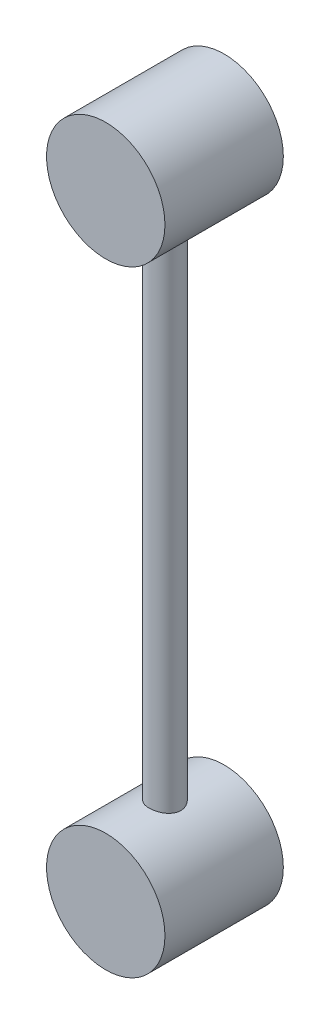
SolidWorks part; units mm, degrees
ref_plane "Front Plane" through (0, 0, 0) normal (0, 0, 1) x (1, 0, 0)
ref_plane "Top Plane" through (0, 0, 0) normal (0, 1, 0) x (1, 0, 0)
ref_plane "Right Plane" through (0, 0, 0) normal (1, 0, 0) x (0, 0, -1)
sketch "Sketch2" plane through (0, 0, 0) normal (0, 0, 1) x (1, 0, 0)
  circle A0 centre (0, 0) radius 7.5
  dimension "D1" = 15
extrude "Boss-Extrude1" add sketch "Sketch2" along normal mid plane 15
sketch "Sketch3" plane through (0, 0, 7.5) normal (0, 0, 1) x (1, 0, 0)
  line L0 (0, 0) -> (0, -50000) construction
sketch "Sketch4" plane through (0, 0, 0) normal (0, 1, 0) x (1, 0, 0)
  circle A0 centre (0, 0) radius 2
  dimension "D1" = 4
extrude "Boss-Extrude2" add sketch "Sketch4" along normal blind 78
pattern_linear "LPattern1" count 2 spacing 78 along (0, 1, 0) of "Boss-Extrude1"
